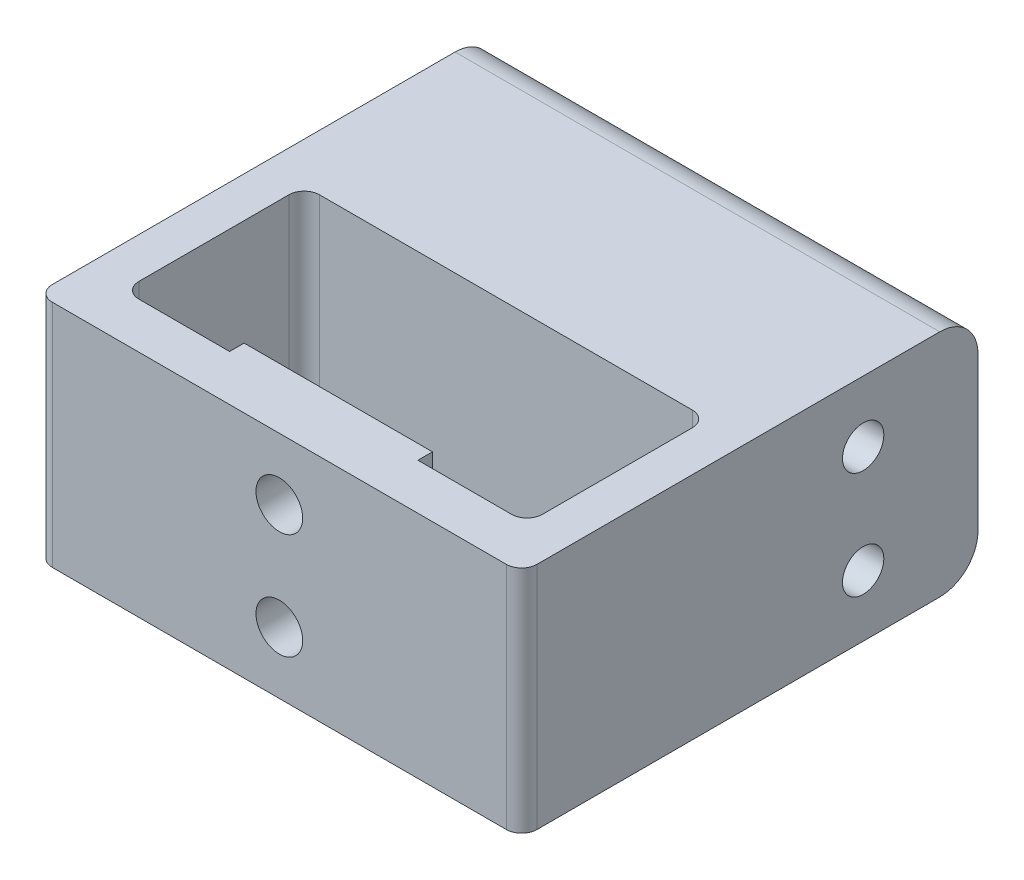
SolidWorks part; units mm, degrees
ref_plane "Plan de face" through (0, 0, 0) normal (0, 0, 1) x (1, 0, 0)
ref_plane "Plan de dessus" through (0, 0, 0) normal (0, 1, 0) x (1, 0, 0)
ref_plane "Plan de droite" through (0, 0, 0) normal (1, 0, 0) x (0, 0, -1)
sketch "Esquisse3" plane through (0, 0, 0) normal (0, 0, 1) x (1, 0, 0)
  circle A0 centre (0, 5.7699) radius 3.05
  circle A1 centre (0, -8.0801) radius 3.05
sketch "Esquisse1" plane through (0, 0, 0) normal (0, 0, 1) x (1, 0, 0)
  line L1 (-12.5, 13.8449) -> (12.1, 13.8449)
  line L2 (-12.5, 13.8449) -> (-12.5, -16.1551)
  line L3 (-12.5, -16.1551) -> (12.1, -16.1551)
  line L4 (12.1, 13.8449) -> (12.1, -16.1551)
  dimension "D1" = 24.6
  dimension "D2" = 30
  dimension "D3" = 12.5
extrude "Boss.-Extru.1" add sketch "Esquisse1" along normal blind 1.9
sketch "Esquisse2" plane through (0, 0, 1.9) normal (0, 0, 1) x (1, 0, 0)
  line L1 (-26.35, 13.8449) -> (26.35, 13.8449)
  line L2 (-26.35, 13.8449) -> (-26.35, -16.1551)
  line L3 (-26.35, -16.1551) -> (26.35, -16.1551)
  line L4 (26.35, 13.8449) -> (26.35, -16.1551)
other "AlignerGroupe1" parameters "D5"=7.665, "D6"=6.2175, "D1"=50.1306, "D2"=29.958, "D3"=30, "D4"=7.5733, "D7"=10.8744, "D8"=11.15, "D9"=13.85, "D10"=8.5
extrude "Boss.-Extru.2" add sketch "Esquisse2" along normal blind 6
sketch "Esquisse4" plane through (-26.35, 0, 0) normal (-1, 0, 0) x (0, 0, 1)
  line L1 (7.9, 13.8449) -> (-21.7, 13.8449)
  line L2 (7.9, 13.8449) -> (7.9, -16.1551)
  line L3 (7.9, -16.1551) -> (-21.7, -16.1551)
  line L4 (-21.7, 13.8449) -> (-21.7, -16.1551)
  dimension "D1" = 29.6
extrude "Boss.-Extru.3" add sketch "Esquisse4" along normal blind 5.3
sketch "Esquisse5" plane through (26.35, 0, 0) normal (1, 0, 0) x (0, 0, -1)
  line L1 (-7.9, 13.8449) -> (21.7, 13.8449)
  line L2 (-7.9, 13.8449) -> (-7.9, -16.1551)
  line L3 (-7.9, -16.1551) -> (21.7, -16.1551)
  line L4 (21.7, 13.8449) -> (21.7, -16.1551)
extrude "Boss.-Extru.4" add sketch "Esquisse5" along normal blind 5.3
sketch "Esquisse6" plane through (0, 0, -21.7) normal (0, 0, -1) x (-1, 0, 0)
  line L1 (-31.65, 13.8449) -> (31.65, 13.8449)
  line L2 (-31.65, 13.8449) -> (-31.65, -16.1551)
  line L3 (-31.65, -16.1551) -> (31.65, -16.1551)
  line L4 (31.65, 13.8449) -> (31.65, -16.1551)
extrude "Boss.-Extru.5" add sketch "Esquisse6" along normal blind 3
fillet "Congé1" radius 2 6 edges at (26.35, -1.1551, -21.7) (-31.65, -1.1551, 7.9) (31.65, -1.1551, 7.9) (-26.35, -1.1551, 1.9) (-26.35, -1.1551, -21.7) (26.35, -1.1551, 1.9)
sketch "Esquisse7" plane through (0, 0, -24.7) normal (0, 0, -1) x (-1, 0, 0)
  line L1 (-31.65, 13.8449) -> (31.65, 13.8449)
  line L2 (-31.65, 13.8449) -> (-31.65, -16.1551)
  line L3 (-31.65, -16.1551) -> (31.65, -16.1551)
  line L4 (31.65, 13.8449) -> (31.65, -16.1551)
extrude "Boss.-Extru.6" add sketch "Esquisse7" along normal blind 27
fillet "Congé3" radius 5 2 edges at (0, -16.1551, -51.7) (0, 13.8449, -51.7)
sketch "Esquisse8" plane through (-31.65, 0, 0) normal (-1, 0, 0) x (0, 0, 1)
  line L1 (-51.7, -11.1551) -> (-51.7, 8.8449) construction
  line L2 (5.9, 13.8449) -> (-46.7, 13.8449) construction
  line L3 (-46.7, -16.1551) -> (5.9, -16.1551) construction
  circle A0 centre (-36.7, 5.8449) radius 2.7
  circle A1 centre (-36.7, -8.1551) radius 2.7
  dimension "D5" = 5.4
  dimension "D6" = 5.4
  dimension "D1" = 15
  dimension "D2" = 15
  dimension "D3" = 8
  dimension "D4" = 8
extrude "Enlèv. mat.-Extru.2" cut sketch "Esquisse3" along normal blind 26
extrude "Enlèv. mat.-Extru.3" cut sketch "Esquisse8" against normal blind 68
